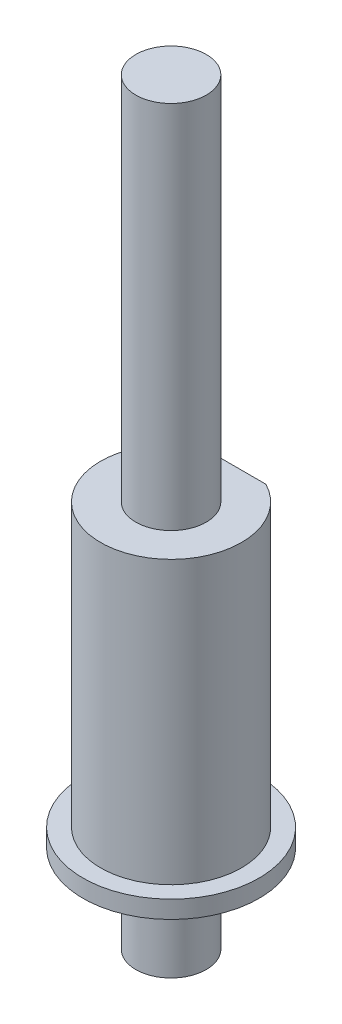
SolidWorks part; units mm, degrees
ref_plane "前视基准面" through (0, 0, 0) normal (0, 0, 1) x (1, 0, 0)
ref_plane "上视基准面" through (0, 0, 0) normal (0, 1, 0) x (1, 0, 0)
ref_plane "右视基准面" through (0, 0, 0) normal (1, 0, 0) x (0, 0, -1)
sketch "草图1" plane through (0, 0, 0) normal (0, 1, 0) x (1, 0, 0)
  circle A0 centre (0, 0) radius 1
extrude "凸台-拉伸1" add sketch "草图1" along normal blind 21.5
sketch "草图2" plane through (0, 0, 0) normal (0, -1, 0) x (1, 0, 0)
  circle A0 centre (0, 0) radius 1
  circle A1 centre (0, 0) radius 2.5
extrude "凸台-拉伸2" add sketch "草图2" against normal blind 0.5 from offset 2.5 offset against normal yes
sketch "草图3" plane through (0, 3, 0) normal (0, 1, 0) x (-1, 0, 0)
  line L0 (-0.9119, -1.78) -> (0.9119, -1.78)
  circle A0 centre (0, 0) radius 1
  arc A1 (0.9119, -1.78) -> (-0.9119, -1.78) centre (0, 0) ccw
  dimension "D1" = 1.78
extrude "凸台-拉伸3" add sketch "草图3" along normal blind 8
